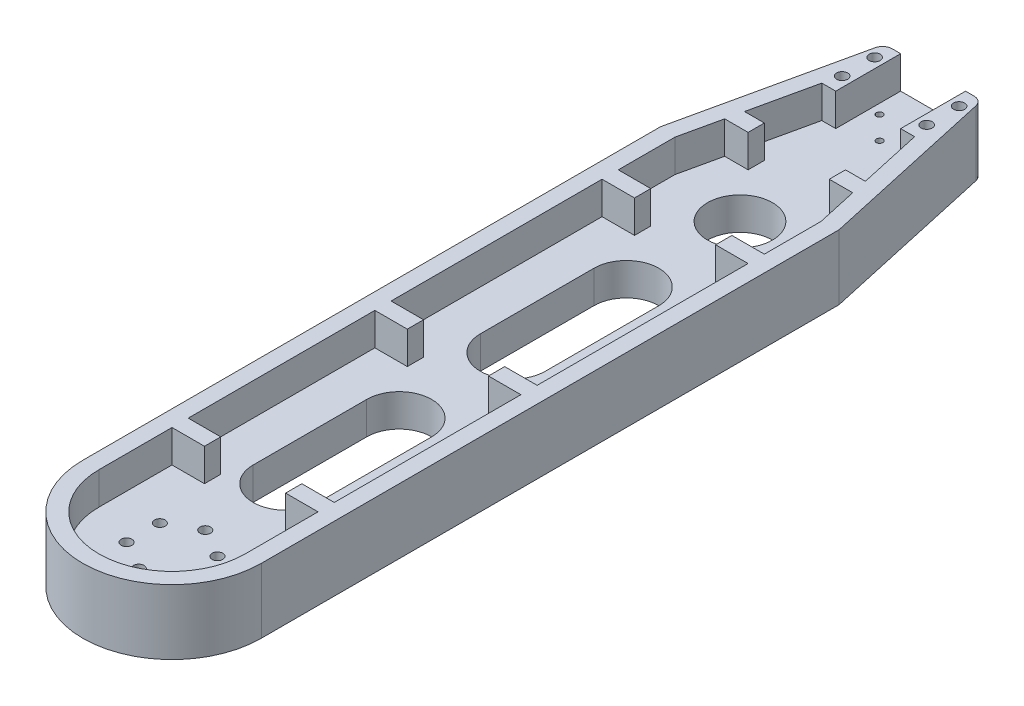
SolidWorks part; units mm, degrees
ref_plane "前视基准面" through (0, 0, 0) normal (0, 0, 1) x (1, 0, 0)
ref_plane "上视基准面" through (0, 0, 0) normal (0, 1, 0) x (1, 0, 0)
ref_plane "右视基准面" through (0, 0, 0) normal (1, 0, 0) x (0, 0, -1)
sketch "草图1" plane through (0, 0, 0) normal (0, 1, 0) x (1, 0, 0)
  line L0 (-27.5, 0) -> (-27.5, 178.006)
  line L1 (0, 0) -> (0, 245) construction
  line L2 (27.5, 178.006) -> (27.5, 0)
  line L4 (0, 105) -> (0, 140) construction
  line L9 (-27.5, 178.006) -> (-15, 234.5)
  line L15 (0, 35) -> (0, 70) construction
  line L17 (-10, 105) -> (-10, 140)
  line L18 (10, 105) -> (10, 140)
  line L19 (-10, 214.5) -> (10, 214.5) construction
  line L22 (-10, 35) -> (-10, 70)
  line L23 (10, 35) -> (10, 70)
  line L24 (-10, 214.5) -> (-10, 254.5) construction
  line L25 (-10, 254.5) -> (10, 254.5) construction
  line L26 (10, 214.5) -> (10, 254.5) construction
  line L27 (-10, 214.5) -> (10, 254.5) construction
  line L28 (-10, 254.5) -> (10, 214.5) construction
  line L29 (27.5, 178.006) -> (15, 234.5)
  line L30 (-15, 234.5) -> (15, 234.5)
  arc A3 (-27.5, 0) -> (27.5, 0) centre (0, 0) ccw
  circle A4 centre (0, 0) radius 10.25 construction
  circle A5 centre (0, 10.25) radius 1.65
  circle A6 centre (8.8768, 5.125) radius 1.65
  circle A7 centre (8.8768, -5.125) radius 1.65
  circle A8 centre (0, -10.25) radius 1.65
  circle A9 centre (-8.8768, -5.125) radius 1.65
  circle A10 centre (-8.8768, 5.125) radius 1.65
  arc A22 (-10, 105) -> (10, 105) centre (0, 105) ccw
  arc A23 (10, 140) -> (-10, 140) centre (0, 140) ccw
  arc A26 (-10, 35) -> (10, 35) centre (0, 35) ccw
  arc A27 (10, 70) -> (-10, 70) centre (0, 70) ccw
  circle A28 centre (0, 175) radius 10
  circle A29 centre (0, 175) radius 27.5 construction
  point P4 (0, 0)
  point P22 (0, 0)
  point P23 (0, 234.5)
  point P28 (0, 52.5)
  point P41 (-10, 234.5)
  point P50 (0, 122.5)
  dimension "D1" = 55
  dimension "D3" = 20.5
  dimension "D4" = 3.3
  dimension "D8" = 5
  dimension "D10" = 35
  dimension "D12" = 20
  dimension "D15" = 30.5
  dimension "D2" = 20
  dimension "D6" = 35
  dimension "D7" = 245
  dimension "D13" = 20
  dimension "D14" = 40
  dimension "D11" = 35
  dimension "D9" = 35
  dimension "D5" = 6
extrude "凸台-拉伸1" add sketch "草图1" along normal blind 10
sketch "草图2" plane through (0, 10, 0) normal (0, 1, 0) x (1, 0, 0)
  line L9 (-22.5, 0) -> (-22.5, 177.4595)
  line L10 (22.5, 177.4595) -> (22.5, 0)
  line L18 (-22.5, 177.4595) -> (-14.3043, 214.5)
  line L19 (-14.3043, 214.5) -> (-10, 214.5)
  line L20 (-10, 214.5) -> (-10, 234.5)
  line L21 (15, 234.5) -> (-15, 234.5) construction
  line L22 (22.5, 177.4595) -> (14.3043, 214.5)
  line L23 (14.3043, 214.5) -> (10, 214.5)
  line L24 (10, 214.5) -> (10, 234.5)
  line L25 (-15, 234.5) -> (-27.5, 178.006) construction
  line L26 (27.5, 178.006) -> (15, 234.5) construction
  arc A3 (-22.5, 0) -> (22.5, 0) centre (0, 0) ccw
  dimension "D1" = 45
  dimension "D2" = 5
  dimension "D3" = 20
  dimension "D4" = 20
extrude "凸台-拉伸2" add sketch "草图2" along normal blind 10
sketch "草图3" plane through (0, 10, 0) normal (0, 1, 0) x (1, 0, 0)
  line L0 (22.5, 177.4595) -> (22.5, 0) construction
  line L1 (-22.5, -22.5) -> (22.5, -22.5) construction
  line L2 (-22.5, -22.5) -> (-22.5, 22.5) construction
  line L3 (-22.5, 22.5) -> (22.5, 22.5) construction
  line L4 (22.5, -22.5) -> (22.5, 22.5) construction
  line L5 (-22.5, -22.5) -> (22.5, 22.5) construction
  line L6 (-22.5, 22.5) -> (22.5, -22.5) construction
  line L7 (0, 95) -> (0, 80) construction
  line L8 (-22.5, 22.5) -> (-12.5, 22.5)
  line L9 (-22.5, 22.5) -> (-22.5, 27.5)
  line L10 (-22.5, 27.5) -> (-12.5, 27.5)
  line L11 (-12.5, 22.5) -> (-12.5, 27.5)
  line L12 (22.5, 22.5) -> (12.5, 22.5)
  line L13 (22.5, 22.5) -> (22.5, 27.5)
  line L14 (22.5, 27.5) -> (12.5, 27.5)
  line L15 (12.5, 22.5) -> (12.5, 27.5)
  line L16 (-12.5, 87.5) -> (12.5, 87.5) construction
  line L17 (-22.5, 0) -> (-22.5, 177.4595) construction
  line L18 (-22.5, 85) -> (-12.5, 85)
  line L19 (-22.5, 85) -> (-22.5, 90)
  line L20 (-22.5, 90) -> (-12.5, 90)
  line L21 (-12.5, 85) -> (-12.5, 90)
  line L22 (0, 165) -> (0, 150) construction
  line L23 (22.5, 85) -> (12.5, 85)
  line L24 (22.5, 85) -> (22.5, 90)
  line L25 (22.5, 90) -> (12.5, 90)
  line L26 (12.5, 85) -> (12.5, 90)
  line L27 (-12.5, 157.5) -> (12.5, 157.5) construction
  line L28 (22.5, 177.4595) -> (22.5, 0) construction
  line L29 (-22.5, 155) -> (-12.5, 155)
  line L30 (-22.5, 155) -> (-22.5, 160)
  line L31 (-22.5, 160) -> (-12.5, 160)
  line L32 (-12.5, 155) -> (-12.5, 160)
  line L33 (22.5, 155) -> (12.5, 155)
  line L34 (22.5, 155) -> (22.5, 160)
  line L35 (22.5, 160) -> (12.5, 160)
  line L36 (12.5, 155) -> (12.5, 160)
  line L37 (0, 185) -> (0, 192.5) construction
  line L38 (-12.5, 192.5) -> (12.5, 192.5) construction
  line L39 (-22.5, 177.4595) -> (-14.3043, 214.5) construction
  line L40 (-19.7252, 190) -> (-12.5, 190)
  line L41 (-19.7252, 190) -> (-19.7252, 195)
  line L42 (-19.7252, 195) -> (-12.5, 195)
  line L43 (-12.5, 190) -> (-12.5, 195)
  line L44 (19.7252, 195) -> (12.5, 195)
  line L45 (12.5, 190) -> (12.5, 195)
  line L46 (19.7252, 190) -> (12.5, 190)
  line L47 (19.7252, 190) -> (19.7252, 195)
  arc A0 (-10, 105) -> (10, 105) centre (0, 105) ccw construction
  arc A1 (10, 70) -> (-10, 70) centre (0, 70) ccw construction
  arc A3 (10, 140) -> (-10, 140) centre (0, 140) ccw construction
  circle A4 centre (0, 175) radius 10 construction
  point P0 (0, 0)
  point P24 (0, 87.5)
  point P45 (0, 157.5)
  dimension "D1" = 5
  dimension "D2" = 10
  dimension "D3" = 7.5
extrude "凸台-拉伸3" add sketch "草图3" along normal up to surface (10 mm away) up to face at (0, 20, -153.5582)
sketch "草图4" plane through (0, 20, 0) normal (0, 1, 0) x (1, 0, 0)
  line L0 (-13.0167, 234.5) -> (-13.0167, 229.5) construction
  line L2 (-13.0167, 229.5) -> (-13.0167, 219.5) construction
  line L3 (-13.0167, 219.5) -> (-13.0167, 214.5) construction
  line L4 (-14.3043, 214.5) -> (-10, 214.5) construction
  line L5 (13.0167, 234.5) -> (13.0167, 229.5) construction
  line L7 (13.0167, 229.5) -> (13.0167, 219.5) construction
  line L8 (13.0167, 219.5) -> (13.0167, 214.5) construction
  line L9 (14.3043, 214.5) -> (10, 214.5) construction
  line L10 (-13.0167, 229.5) -> (-10, 229.5) construction
  line L11 (-10, 214.5) -> (-10, 234.5) construction
  line L12 (-13.0167, 229.5) -> (-15.9621, 230.1517) construction
  line L13 (-15, 234.5) -> (-27.5, 178.006) construction
  line L14 (-13.0167, 234.5) -> (-10, 234.5) construction
  line L15 (13.0167, 234.5) -> (10, 234.5) construction
  circle A0 centre (-13.0167, 229.5) radius 1.7
  circle A1 centre (-13.0167, 219.5) radius 1.7
  circle A2 centre (13.0167, 229.5) radius 1.7
  circle A3 centre (13.0167, 219.5) radius 1.7
  dimension "D2" = 3.4
  dimension "D1" = 5
extrude "切除-拉伸1" cut sketch "草图4" against normal through all
sketch "草图5" plane through (0, 10, 0) normal (0, 1, 0) x (1, 0, 0)
  line L0 (-10, 214.5) -> (10, 214.5) construction
  line L1 (10, 214.5) -> (10, 234.5) construction
  line L2 (14.3043, 214.5) -> (10, 214.5) construction
  line L3 (0, 214.5) -> (0, 218) construction
  line L4 (0, 218) -> (0, 225) construction
  line L5 (0, 225) -> (7, 225) construction
  circle A0 centre (0, 218) radius 1
  circle A1 centre (7, 225) radius 1
  circle A2 centre (-7, 225) radius 1
  dimension "D4" = 2
  dimension "D1" = 7
  dimension "D2" = 7
  dimension "D3" = 3.5
extrude "切除-拉伸2" cut sketch "草图5" against normal through all
sketch "草图7" plane through (0, 0, 0) normal (0, -1, 0) x (1, 0, 0)
  circle A0 centre (0, -218) radius 2.75
  circle A1 centre (-7, -225) radius 2.75
  circle A2 centre (7, -225) radius 2.75
  dimension "D1" = 5.5
extrude "切除-拉伸3" cut sketch "草图7" against normal blind 7.5
fillet "圆角2" radius 3 2 edges at (15, 10, -234.5) (-15, 10, -234.5)
